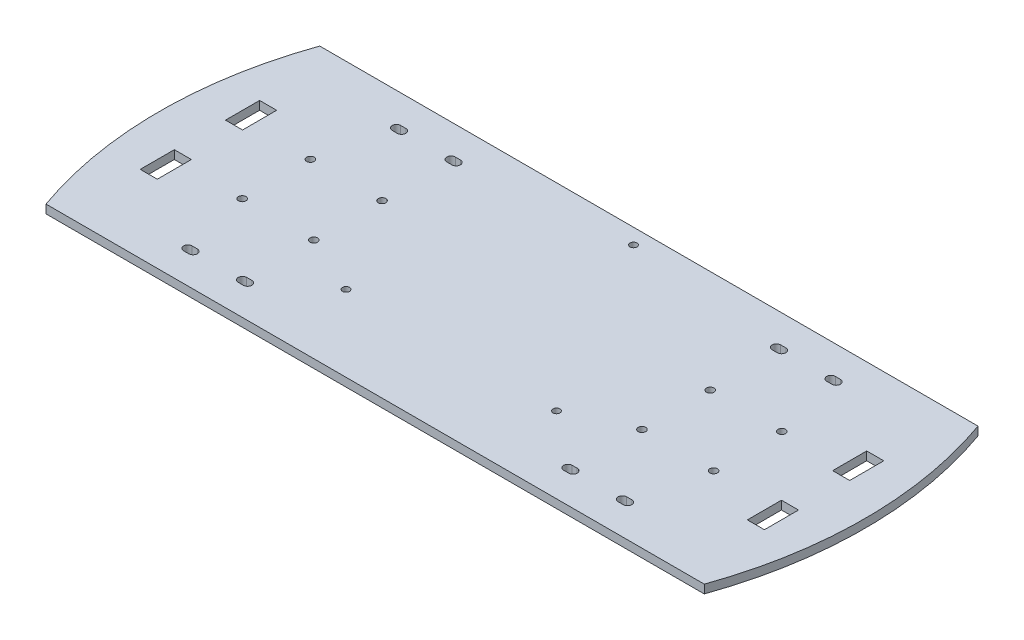
SolidWorks part; units mm, degrees
ref_plane "前基準面" through (0, 0, 0) normal (0, 0, 1) x (1, 0, 0)
ref_plane "上基準面" through (0, 0, 0) normal (0, 1, 0) x (1, 0, 0)
ref_plane "右基準面" through (0, 0, 0) normal (1, 0, 0) x (0, 0, -1)
sketch "草圖1" plane through (0, 0, 0) normal (0, 1, 0) x (1, 0, 0)
  line L0 (0, 0) -> (0, 89.692) construction
  line L1 (0, 0) -> (84.1488, -48.5834) construction
  line L2 (0, 0) -> (-79.0259, -45.6256) construction
  line L3 (183, -15) -> (173, -15)
  line L4 (193, -80.25) -> (-193, -80.25)
  line L5 (193, -80.25) -> (193, 80.25) construction
  line L6 (193, 80.25) -> (-193, 80.25)
  line L7 (-193, -80.25) -> (-193, 80.25) construction
  line L8 (0, 80.25) -> (0, -80.25) construction
  line L9 (193, 0) -> (-193, 0) construction
  line L10 (-155, -100) -> (155, -100) construction
  line L11 (-155, -100) -> (-155, 100) construction
  line L12 (-155, 100) -> (155, 100) construction
  line L13 (155, -100) -> (155, 100) construction
  line L14 (0, 100) -> (0, -100) construction
  line L15 (-155, 0) -> (155, 0) construction
  line L16 (-156, -22) -> (-172, -22) construction
  line L17 (-156, -22) -> (-156, 22) construction
  line L18 (-156, 22) -> (-172, 22) construction
  line L19 (-172, -22) -> (-172, 22) construction
  line L20 (-173, -50) -> (-183, -50) construction
  line L21 (-156, 0) -> (-172, 0) construction
  line L22 (-173, -50) -> (-173, 50) construction
  line L23 (-173, 50) -> (-183, 50) construction
  line L24 (-183, -50) -> (-183, 50) construction
  line L25 (-183, -35) -> (-173, -35)
  line L26 (-173, 0) -> (-183, 0) construction
  line L27 (-183, -35) -> (-183, -15)
  line L28 (-183, -15) -> (-173, -15)
  line L29 (-173, -35) -> (-173, -15)
  line L30 (-183, 15) -> (-173, 15)
  line L31 (-183, 15) -> (-183, 35)
  line L32 (-183, 35) -> (-173, 35)
  line L33 (-173, 15) -> (-173, 35)
  line L34 (173, -35) -> (173, -15)
  line L35 (183, -35) -> (173, -35)
  line L36 (183, -35) -> (183, -15)
  line L37 (183, 35) -> (173, 35)
  line L38 (173, 15) -> (173, 35)
  line L39 (183, 15) -> (173, 15)
  line L40 (183, 15) -> (183, 35)
  circle A0 centre (0, 71.25) radius 4 construction
  circle A4 centre (61.7043, -35.625) radius 4 construction
  circle A6 centre (-61.7043, -35.625) radius 4 construction
  circle A7 centre (0, 71.25) radius 2.05
  circle A8 centre (61.7043, -35.625) radius 2.05
  circle A9 centre (-61.7043, -35.625) radius 2.05
  circle A11 centre (0, 0) radius 75.25 construction
  circle A12 centre (0, 0) radius 80.25 construction
  arc A13 (-193, 80.25) -> (-193, -80.25) centre (33.1856, 0) ccw
  arc A14 (193, 80.25) -> (193, -80.25) centre (-33.1856, 0) cw
  point P22 (-164, 0)
  point P33 (-178, 0)
  point P62 (206.8144, 0)
  point P63 (-206.8144, 0)
  dimension "D3" = 4.1
  dimension "D4" = 8
  dimension "D5" = 71.25
  dimension "D6" = 120
  dimension "D1" = 120
  dimension "D9" = 5
  dimension "D22" = 4.1
  dimension "D23" = 240
  dimension "D2" = 71.25
  dimension "D7" = 71.25
  dimension "D8" = 310
  dimension "D10" = 200
  dimension "D11" = 16
  dimension "D12" = 44
  dimension "D13" = 1
  dimension "D14" = 10
  dimension "D15" = 100
  dimension "D16" = 1
  dimension "D17" = 10
  dimension "D18" = 386
  dimension "D19" = 20
  dimension "D20" = 15
  dimension "D21" = 15
  dimension "D24" = 413.6287
extrude "填料-伸長1" add sketch "草圖1" along normal blind 5
sketch "草圖2" plane through (0, 5, 0) normal (0, 1, 0) x (1, 0, 0)
  line L0 (-232.8206, 0) -> (229.5414, 0) construction
  line L1 (0, 102.2006) -> (0, -106.5728) construction
  line L2 (-54.2, 28.5) -> (-151.2, 28.5)
  line L3 (-54.2, 28.5) -> (-54.2, -28.5)
  line L4 (-54.2, -28.5) -> (-151.2, -28.5)
  line L5 (-151.2, 28.5) -> (-151.2, -28.5)
  line L6 (-102.7, -28.5) -> (-102.7, 28.5) construction
  line L7 (-54.2, 0) -> (-151.2, 0) construction
  line L8 (-173, -35) -> (-173, -15) construction
  line L9 (-172.2, 4) -> (-151.2, 4)
  line L10 (-172.2, 4) -> (-172.2, -4) construction
  line L11 (-172.2, -4) -> (-151.2, -4)
  line L12 (-151.2, 4) -> (-151.2, -4)
  line L13 (-172, 15) -> (-154.9, 15)
  line L14 (-172.2, 0) -> (-151.2, 0) construction
  line L15 (-172, 15) -> (-172, -15)
  line L16 (-172, -15) -> (-154.9, -15)
  line L17 (-154.9, 15) -> (-154.9, -15)
  line L18 (172, -15) -> (154.9, -15)
  line L19 (154.9, 15) -> (154.9, -15)
  line L20 (172, 15) -> (154.9, 15)
  line L21 (172, 15) -> (172, -15)
  line L22 (172.2, -4) -> (151.2, -4)
  line L23 (151.2, 4) -> (151.2, -4)
  line L24 (172.2, 4) -> (151.2, 4)
  line L25 (172.2, 4) -> (172.2, -4)
  line L26 (54.2, -28.5) -> (151.2, -28.5)
  line L27 (151.2, 28.5) -> (151.2, -28.5)
  line L28 (54.2, 28.5) -> (151.2, 28.5)
  line L29 (54.2, 28.5) -> (54.2, -28.5)
  line L30 (193, 80.25) -> (-193, 80.25) construction
  line L31 (-183, 80.25) -> (-173, 80.25) construction
  line L32 (-183, 80.25) -> (-183, -80.25) construction
  line L33 (-183, -80.25) -> (-173, -80.25) construction
  line L34 (-173, 80.25) -> (-173, -80.25) construction
  line L35 (-193, -80.25) -> (193, -80.25) construction
  line L36 (-183, 35) -> (-183, 15) construction
  line L37 (183, 80.25) -> (183, -80.25) construction
  line L38 (173, 80.25) -> (173, -80.25) construction
  point P3 (-102.7, 0)
  point P9 (-160.2566, 0)
  point P16 (-172, 0)
  dimension "D1" = 97
  dimension "D2" = 57
  dimension "D3" = 21
  dimension "D4" = 8
  dimension "D5" = 30
  dimension "D6" = 17.1
  dimension "D7" = 20.8
  dimension "D8" = 1
  dimension "D9" = 10
sketch "草圖4" plane through (0, 5, 0) normal (0, 1, 0) x (1, 0, 0)
  line L0 (0, 102.2006) -> (0, -106.5728) construction
  line L1 (-86.2, -32.5) -> (-154.2, -32.5) construction
  line L2 (-86.2, -32.5) -> (-86.2, 32.5) construction
  line L3 (-86.2, 32.5) -> (-154.2, 32.5) construction
  line L4 (-154.2, -32.5) -> (-154.2, 32.5) construction
  line L5 (-232.8206, 0) -> (229.5414, 0) construction
  line L6 (-151.2, 32.5) -> (-151.2, -32.5) construction
  line L7 (-151.2, 28.5) -> (-151.2, -28.5) construction
  line L8 (-138.2, -20) -> (-96.2, -20) construction
  line L9 (-138.2, -17.9) -> (-96.2, -17.9) construction
  line L10 (-138.2, -22.1) -> (-96.2, -22.1) construction
  line L11 (-232.8206, 0) -> (229.5414, 0) construction
  line L12 (-138.2, 20) -> (-96.2, 20) construction
  line L13 (-138.2, 17.9) -> (-96.2, 17.9) construction
  line L14 (-138.2, 22.1) -> (-96.2, 22.1) construction
  line L15 (-138.2, 20) -> (-138.2, -20) construction
  line L16 (-136, 20) -> (-136, -20) construction
  line L17 (-140.4, 20) -> (-140.4, -20) construction
  line L18 (-96.2, 20) -> (-96.2, -20) construction
  line L19 (-94, 20) -> (-94, -20) construction
  line L20 (-98.4, 20) -> (-98.4, -20) construction
  line L21 (-173, 80.25) -> (-173, -80.25) construction
  line L22 (0, 102.2006) -> (0, -106.5728) construction
  line L23 (-96.9, 61.15) -> (-93.9, 61.15) construction
  line L24 (-96.9, 63.65) -> (-93.9, 63.65)
  line L25 (-96.9, 58.65) -> (-93.9, 58.65)
  line L26 (-128.9, 61.15) -> (-125.9, 61.15) construction
  line L27 (-128.9, 63.65) -> (-125.9, 63.65)
  line L28 (-128.9, 58.65) -> (-125.9, 58.65)
  line L29 (-83.8, 70.25) -> (-139, 70.25) construction
  line L30 (-83.8, 70.25) -> (-83.8, 52.05) construction
  line L31 (-83.8, 52.05) -> (-139, 52.05) construction
  line L32 (-139, 70.25) -> (-139, 52.05) construction
  line L33 (-111.4, 52.05) -> (-111.4, 70.25) construction
  line L34 (-83.8, 61.15) -> (-139, 61.15) construction
  line L35 (193, 80.25) -> (-193, 80.25) construction
  line L36 (-96.9, -61.15) -> (-93.9, -61.15) construction
  line L37 (-96.9, -63.65) -> (-93.9, -63.65)
  line L38 (-96.9, -58.65) -> (-93.9, -58.65)
  line L39 (-128.9, -61.15) -> (-125.9, -61.15) construction
  line L40 (-128.9, -63.65) -> (-125.9, -63.65)
  line L41 (-128.9, -58.65) -> (-125.9, -58.65)
  line L42 (-83.8, -70.25) -> (-83.8, -52.05) construction
  line L43 (-83.8, -70.25) -> (-139, -70.25) construction
  line L44 (-139, -70.25) -> (-139, -52.05) construction
  line L45 (-83.8, -52.05) -> (-139, -52.05) construction
  line L46 (96.9, -61.15) -> (93.9, -61.15) construction
  line L47 (96.9, -63.65) -> (93.9, -63.65)
  line L48 (96.9, -58.65) -> (93.9, -58.65)
  line L49 (128.9, -61.15) -> (125.9, -61.15) construction
  line L50 (128.9, -63.65) -> (125.9, -63.65)
  line L51 (128.9, -58.65) -> (125.9, -58.65)
  line L52 (96.9, 61.15) -> (93.9, 61.15) construction
  line L53 (96.9, 63.65) -> (93.9, 63.65)
  line L54 (96.9, 58.65) -> (93.9, 58.65)
  line L55 (128.9, 61.15) -> (125.9, 61.15) construction
  line L56 (128.9, 63.65) -> (125.9, 63.65)
  line L57 (128.9, 58.65) -> (125.9, 58.65)
  line L58 (83.8, 61.15) -> (139, 61.15) construction
  line L59 (111.4, 52.05) -> (111.4, 70.25) construction
  line L60 (139, 70.25) -> (139, 52.05) construction
  line L61 (83.8, 52.05) -> (139, 52.05) construction
  line L62 (83.8, 70.25) -> (83.8, 52.05) construction
  line L63 (83.8, 70.25) -> (139, 70.25) construction
  line L64 (83.8, -52.05) -> (139, -52.05) construction
  line L65 (139, -70.25) -> (139, -52.05) construction
  line L66 (83.8, -70.25) -> (139, -70.25) construction
  line L67 (83.8, -70.25) -> (83.8, -52.05) construction
  arc A0 (-138.2, -17.9) -> (-138.2, -22.1) centre (-138.2, -20) ccw construction
  arc A1 (-96.2, -22.1) -> (-96.2, -17.9) centre (-96.2, -20) ccw construction
  arc A2 (-138.2, 17.9) -> (-138.2, 22.1) centre (-138.2, 20) cw construction
  arc A3 (-96.2, 22.1) -> (-96.2, 17.9) centre (-96.2, 20) cw construction
  arc A4 (-136, 20) -> (-140.4, 20) centre (-138.2, 20) ccw construction
  arc A5 (-140.4, -20) -> (-136, -20) centre (-138.2, -20) ccw construction
  arc A6 (-94, 20) -> (-98.4, 20) centre (-96.2, 20) ccw construction
  arc A7 (-98.4, -20) -> (-94, -20) centre (-96.2, -20) ccw construction
  circle A12 centre (-138.2, 20) radius 2.2
  circle A13 centre (-96.2, 20) radius 2.2
  circle A14 centre (-96.2, -20) radius 2.2
  circle A15 centre (-138.2, -20) radius 2.2
  circle A16 centre (96.2, -20) radius 2.2
  circle A17 centre (138.2, -20) radius 2.2
  circle A18 centre (96.2, 20) radius 2.2
  circle A19 centre (138.2, 20) radius 2.2
  arc A20 (-96.9, 63.65) -> (-96.9, 58.65) centre (-96.9, 61.15) ccw
  arc A21 (-93.9, 58.65) -> (-93.9, 63.65) centre (-93.9, 61.15) ccw
  arc A22 (-128.9, 63.65) -> (-128.9, 58.65) centre (-128.9, 61.15) ccw
  arc A23 (-125.9, 58.65) -> (-125.9, 63.65) centre (-125.9, 61.15) ccw
  arc A24 (-96.9, -63.65) -> (-96.9, -58.65) centre (-96.9, -61.15) cw
  arc A25 (-93.9, -58.65) -> (-93.9, -63.65) centre (-93.9, -61.15) cw
  arc A26 (-128.9, -63.65) -> (-128.9, -58.65) centre (-128.9, -61.15) cw
  arc A27 (-125.9, -58.65) -> (-125.9, -63.65) centre (-125.9, -61.15) cw
  arc A28 (96.9, -63.65) -> (96.9, -58.65) centre (96.9, -61.15) ccw
  arc A29 (93.9, -58.65) -> (93.9, -63.65) centre (93.9, -61.15) ccw
  arc A30 (128.9, -63.65) -> (128.9, -58.65) centre (128.9, -61.15) ccw
  arc A31 (125.9, -58.65) -> (125.9, -63.65) centre (125.9, -61.15) ccw
  arc A32 (96.9, 63.65) -> (96.9, 58.65) centre (96.9, 61.15) cw
  arc A33 (93.9, 58.65) -> (93.9, 63.65) centre (93.9, 61.15) cw
  arc A34 (128.9, 63.65) -> (128.9, 58.65) centre (128.9, 61.15) cw
  arc A35 (125.9, 58.65) -> (125.9, 63.65) centre (125.9, 61.15) cw
  point P4 (-86.2, 0)
  point P13 (-117.2, -20)
  point P18 (-138.2, 0)
  point P21 (-117.2, 20)
  point P32 (-96.2, 0)
  point P43 (-95.4, 61.15)
  point P63 (-127.4, 61.15)
  point P71 (-123.4, 61.15)
  point P72 (-99.4, 61.15)
  point P73 (-131.4, 61.15)
  point P74 (-91.4, 61.15)
  point P80 (-111.4, 61.15)
  point P98 (-95.4, -61.15)
  point P105 (-127.4, -61.15)
  point P116 (95.4, -61.15)
  point P123 (127.4, -61.15)
  point P130 (95.4, 61.15)
  point P137 (127.4, 61.15)
  point P150 (111.4, 61.15)
  dimension "D7" = 2.1
  dimension "D8" = 2.2
  dimension "D9" = 4.4
  dimension "D1" = 68
  dimension "D2" = 65
  dimension "D3" = 3
  dimension "D4" = 42
  dimension "D5" = 10
  dimension "D6" = 40
  dimension "D10" = 5
  dimension "D11" = 24
  dimension "D12" = 40
  dimension "D13" = 34
  dimension "D14" = 7.6
  dimension "D15" = 18.2
  dimension "D16" = 10
extrude "除料-伸長1" cut sketch "草圖4" against normal through all
